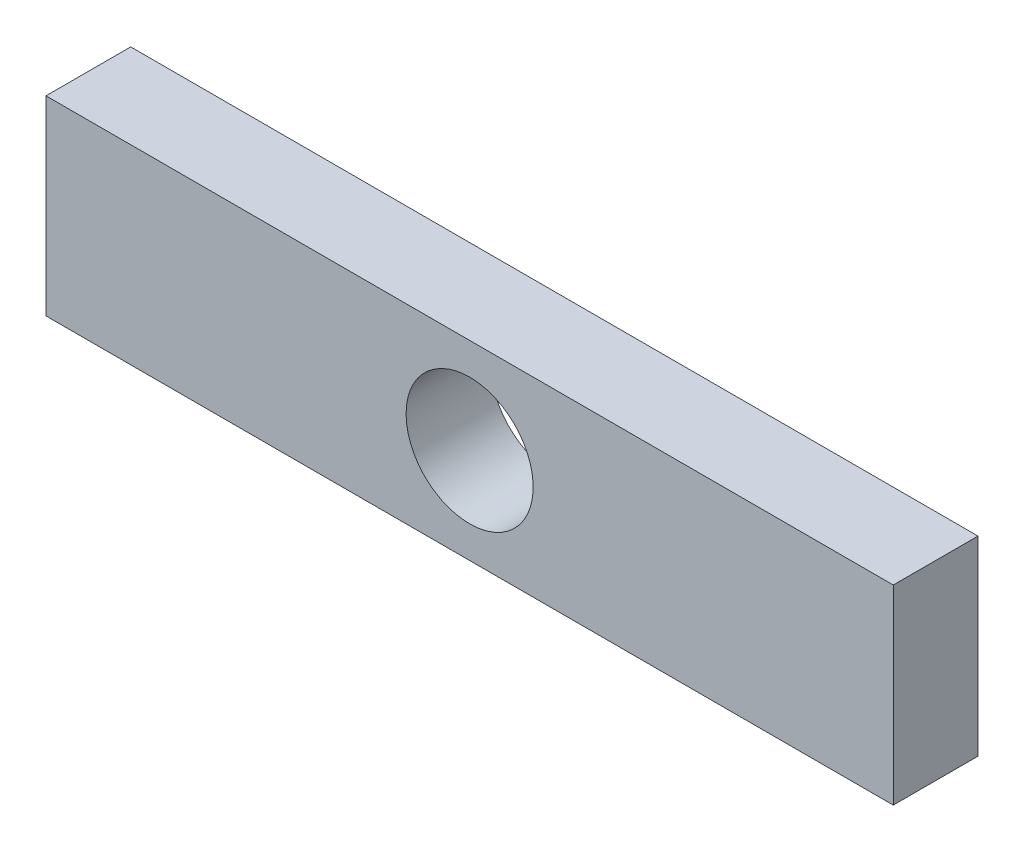
SolidWorks part; units mm, degrees
ref_plane "Front Plane" through (0, 0, 0) normal (0, 0, 1) x (1, 0, 0)
ref_plane "Top Plane" through (0, 0, 0) normal (0, 1, 0) x (1, 0, 0)
ref_plane "Right Plane" through (0, 0, 0) normal (1, 0, 0) x (0, 0, -1)
sketch "Sketch1" plane through (0, 0, 0) normal (0, 1, 0) x (1, 0, 0)
  line L0 (0, 0) -> (40, 0)
  line L1 (40, 0) -> (40, 4)
  line L2 (40, 4) -> (0, 4)
  line L3 (0, 4) -> (0, 0)
  dimension "D1" = 40
  dimension "D2" = 4
extrude "Boss-Extrude1" add sketch "Sketch1" along normal blind 9
sketch "Sketch2" plane through (0, 0, -4) normal (0, 0, -1) x (-1, 0, 0)
  line L0 (-40, 4.5) -> (0, 4.5) construction
  line L1 (-40, 9) -> (-40, 0) construction
  line L2 (0, 9) -> (0, 0) construction
  circle A0 centre (-20, 4.5) radius 3
  point P6 (-20, 4.5)
  point P7 (-20.7637, 4.5)
  point P8 (0, 4.5)
  dimension "D1" = 6
extrude "Cut-Extrude1" cut sketch "Sketch2" against normal up to next
